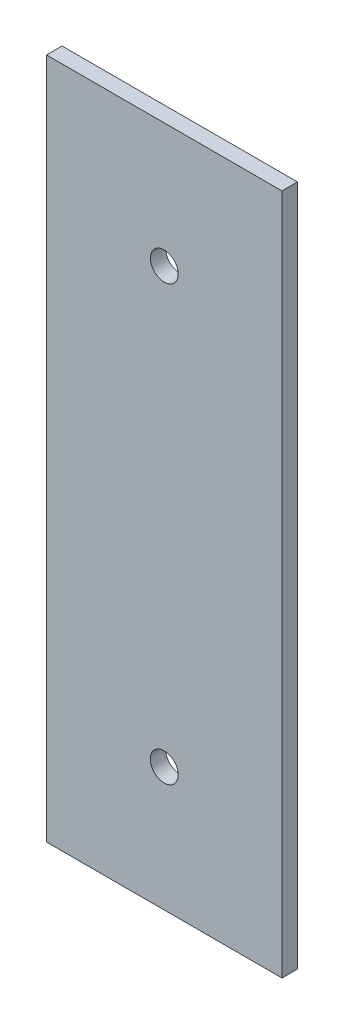
SolidWorks part; units mm, degrees
ref_plane "Front Plane" through (0, 0, 0) normal (0, 0, 1) x (1, 0, 0)
ref_plane "Top Plane" through (0, 0, 0) normal (0, 1, 0) x (1, 0, 0)
ref_plane "Right Plane" through (0, 0, 0) normal (1, 0, 0) x (0, 0, -1)
sketch "Sketch1" plane through (0, 0, 0) normal (0, 0, 1) x (1, 0, 0)
  line L1 (-19, 55) -> (19, 55)
  line L2 (-19, 55) -> (-19, -55)
  line L3 (-19, -55) -> (19, -55)
  line L4 (19, 55) -> (19, -55)
  line L5 (-19, 55) -> (19, -55) construction
  line L6 (-19, -55) -> (19, 55) construction
  point P0 (0, 0)
  dimension "D1" = 110
  dimension "D2" = 38
extrude "Boss-Extrude1" add sketch "Sketch1" along normal blind 2.5
sketch "Sketch2" plane through (0, 0, 2.5) normal (0, 0, 1) x (1, 0, 0)
  line L0 (0, 55) -> (0, 35) construction
  line L1 (19, 55) -> (-19, 55) construction
  line L2 (0, 0) -> (18.407, 0) construction
  circle A0 centre (0, 35) radius 2.25
  circle A1 centre (0, -35) radius 2.25
  dimension "D1" = 20
extrude "Cut-Extrude1" cut sketch "Sketch2" against normal through all both and the other way through all
